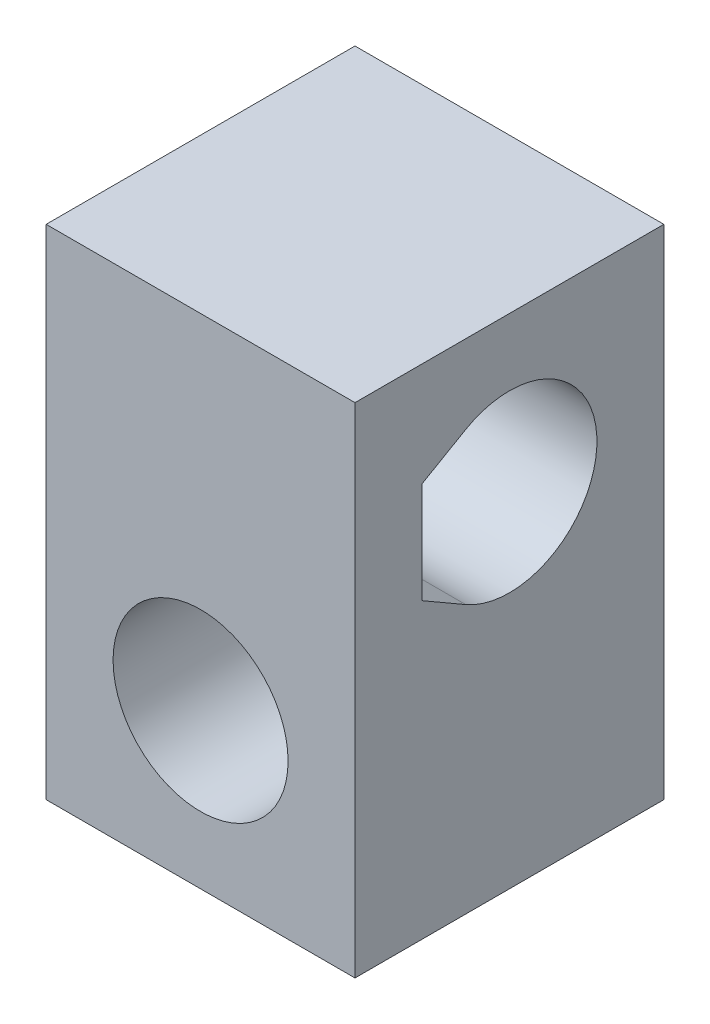
SolidWorks part; units mm, degrees
ref_plane "Piano frontale" through (0, 0, 0) normal (0, 0, 1) x (1, 0, 0)
ref_plane "Piano superiore" through (0, 0, 0) normal (0, 1, 0) x (1, 0, 0)
ref_plane "Piano destro" through (0, 0, 0) normal (1, 0, 0) x (0, 0, -1)
sketch "Schizzo1" plane through (0, 0, 0) normal (0, 0, 1) x (1, 0, 0)
  line L0 (0, 12.1) -> (0, -12.1) construction
  line L1 (-7.5, -12.1) -> (7.5, -12.1)
  line L2 (-7.5, -12.1) -> (-7.5, 12.1)
  line L3 (-7.5, 12.1) -> (7.5, 12.1)
  line L4 (7.5, -12.1) -> (7.5, 12.1)
  line L5 (-7.5, -12.1) -> (7.5, 12.1) construction
  line L6 (-7.5, 12.1) -> (7.5, -12.1) construction
  line L7 (-7.5, 0) -> (7.5, 0) construction
  circle A0 centre (0, -4.6) radius 4.25
  point P0 (0, 0)
  point P12 (0, -0.35)
  dimension "D1" = 8.5
  dimension "D2" = 15
  dimension "D3" = 7.5
  dimension "D4" = 24.2
extrude "Estrusione-Estrusione1" add sketch "Schizzo1" along normal mid plane 15
sketch "Schizzo2" plane through (-7.5, 0, 0) normal (-1, 0, 0) x (0, 0, 1)
  line L0 (0, 12.1) -> (0, -12.1) construction
  line L1 (7.5, 12.1) -> (-7.5, 12.1) construction
  line L2 (7.5, -12.1) -> (-7.5, -12.1) construction
  line L3 (4.25, 2.1463) -> (4.25, 7.0537)
  line L4 (4.25, 7.0537) -> (2.125, 8.2806)
  line L5 (4.25, 2.1463) -> (2.125, 0.9194)
  arc A0 (2.125, 8.2806) -> (2.125, 0.9194) centre (0, 4.6) ccw
  point P11 (4.25, 4.6)
  dimension "D2" = 8.5
  dimension "D1" = 7.5
  dimension "D3" = 120
extrude "Taglio-Estrusione1" cut sketch "Schizzo2" against normal up to next
